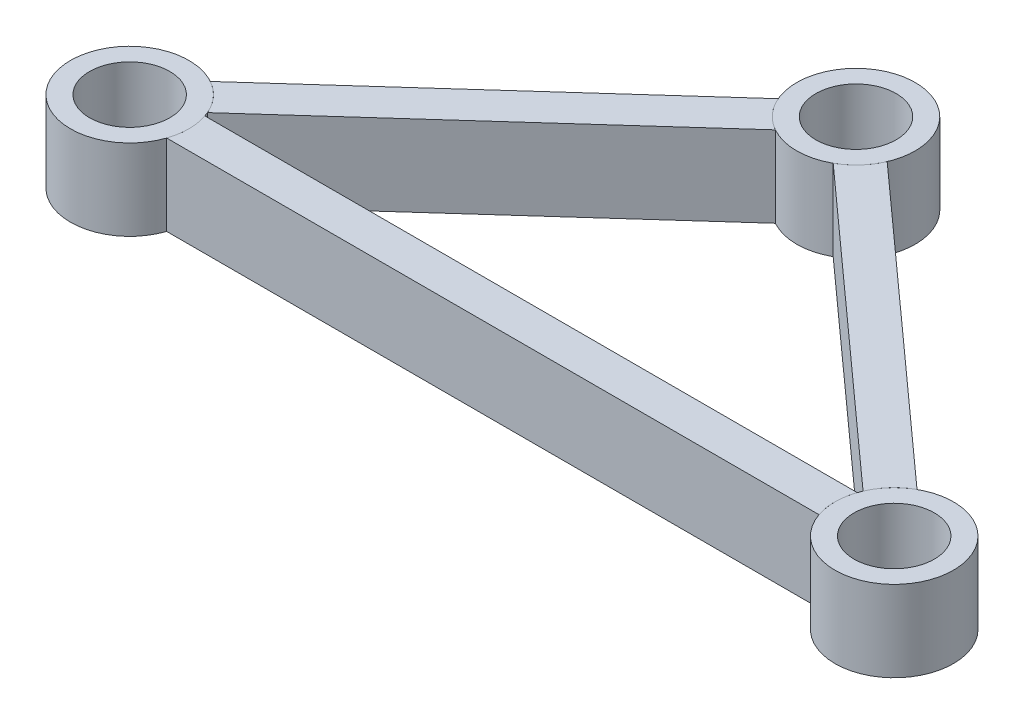
SolidWorks part; units mm, degrees
ref_plane "Front Plane" through (0, 0, 0) normal (0, 0, 1) x (1, 0, 0)
ref_plane "Top Plane" through (0, 0, 0) normal (0, 1, 0) x (1, 0, 0)
ref_plane "Right Plane" through (0, 0, 0) normal (1, 0, 0) x (0, 0, -1)
sketch "Sketch1" plane through (0, 0, 0) normal (0, 1, 0) x (1, 0, 0)
  line L0 (-60, -27) -> (60, -27) construction
  line L1 (60, -27) -> (0, 27) construction
  line L2 (0, 27) -> (-60, -27) construction
  point P4 (0, -27)
  point P7 (30, 0)
  dimension "D1" = 120
  dimension "D2" = 54
sketch "Sketch2" plane through (0, 0, 0) normal (0, 1, 0) x (1, 0, 0)
  circle A0 centre (-60, -27) radius 6.3
  circle A1 centre (0, 27) radius 6.3
  circle A2 centre (60, -27) radius 6.3
  circle A3 centre (60, -27) radius 9.3
  circle A4 centre (0, 27) radius 9.3
  circle A5 centre (-60, -27) radius 9.3
  dimension "D1" = 12.6
  dimension "D2" = 3
extrude "Boss-Extrude1" add sketch "Sketch2" along normal mid plane 12.7
ref_plane "Plane1" through (-6.5128, 0, -5.8615) normal (0.7433, 0, 0.669) x (0.669, 0, -0.7433)
ref_plane "Plane2" through (6.5128, 0, -5.8615) normal (-0.7433, 0, 0.669) x (0.669, 0, 0.7433)
sketch "Sketch8" plane through (0, 0, 0) normal (1, 0, 0) x (0, 0, -1)
  line L1 (-30, 6.35) -> (-24, 6.35)
  line L2 (-30, 6.35) -> (-30, -6.35)
  line L3 (-30, -6.35) -> (-24, -6.35)
  line L4 (-24, 6.35) -> (-24, -6.35)
  line L6 (-17.7, 6.35) -> (-36.3, 6.35) construction
  line L7 (-36.3, -6.35) -> (-17.7, -6.35) construction
  point P8 (-27, 6.35)
  dimension "D1" = 6
sketch "Sketch3" plane through (-6.5128, 0, -5.8615) normal (0.7433, 0, 0.669) x (0.669, 0, -0.7433)
  line L1 (17.0689, 6.35) -> (23.0689, 6.35)
  line L2 (17.0689, 6.35) -> (17.0689, -6.35)
  line L3 (17.0689, -6.35) -> (23.0689, -6.35)
  line L4 (23.0689, 6.35) -> (23.0689, -6.35)
  line L6 (10.7689, -6.35) -> (29.3689, -6.35) construction
  line L7 (29.3689, 6.35) -> (10.7689, 6.35) construction
  point P8 (20.0689, 6.35)
  dimension "D1" = 6
sketch "Sketch4" plane through (6.5128, 0, -5.8615) normal (-0.7433, 0, 0.669) x (0.669, 0, 0.7433)
  line L1 (-23.0689, 6.35) -> (-17.0689, 6.35)
  line L2 (-23.0689, 6.35) -> (-23.0689, -6.35)
  line L3 (-23.0689, -6.35) -> (-17.0689, -6.35)
  line L4 (-17.0689, 6.35) -> (-17.0689, -6.35)
  line L7 (-10.7689, 6.35) -> (-29.3689, 6.35) construction
  line L8 (-29.3689, -6.35) -> (-10.7689, -6.35) construction
  point P8 (-20.0689, 6.35)
  dimension "D1" = 6
extrude "Boss-Extrude3" add sketch "Sketch8" along normal up to next and the other way up to next
extrude "Boss-Extrude4" add sketch "Sketch4" along normal up to next and the other way up to next
extrude "Boss-Extrude5" add sketch "Sketch3" along normal up to next and the other way up to next
equation "\"Width\"=6"
equation "\"D1@Sketch8\"=\"Width\""
equation "\"D1@Sketch4\"=\"Width\""
equation "\"D1@Sketch3\"=\"Width\""
equation "\"D1@Sketch2\"=12.6"
